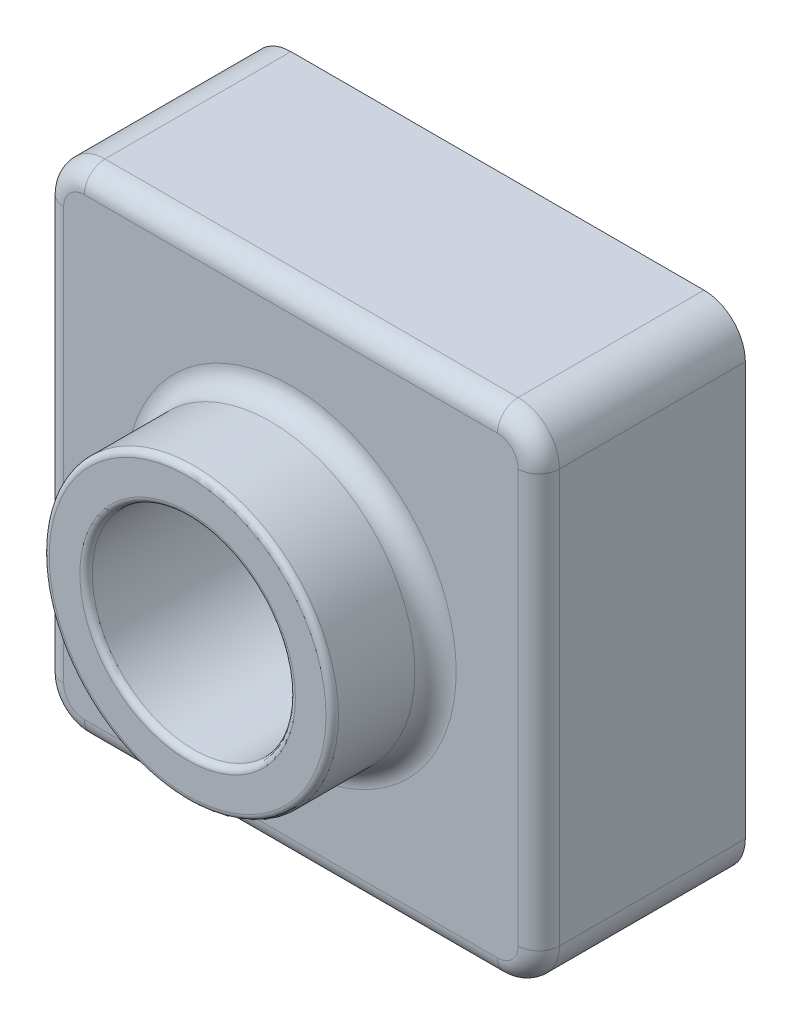
SolidWorks part; units mm, degrees
material "Chrome Stainless Steel"
ref_plane "Front Plane" through (0, 0, 0) normal (0, 0, 1) x (1, 0, 0)
ref_plane "Top Plane" through (0, 0, 0) normal (0, 1, 0) x (1, 0, 0)
ref_plane "Right Plane" through (0, 0, 0) normal (1, 0, 0) x (0, 0, -1)
sketch "Sketch1" plane through (0, 0, 0) normal (0, 0, 1) x (1, 0, 0)
  line L1 (0, 0) -> (-120, 0)
  line L2 (0, 0) -> (0, 120)
  line L3 (0, 120) -> (-120, 120)
  line L4 (-120, 0) -> (-120, 120)
  point P5 (0, 0)
  dimension "D1" = 120
  dimension "D2" = 120
extrude "Boss-Extrude1" add sketch "Sketch1" along normal blind 50
sketch "Sketch3" plane through (0, 0, 50) normal (0, 0, 1) x (1, 0, 0)
  line L0 (0, 120) -> (-120, 120) construction
  line L3 (-120, 120) -> (-120, 0) construction
  circle A0 centre (-60, 60) radius 35
  point P4 (0, 0)
  point P5 (0, 0)
  point P6 (-120, 39.2847)
  dimension "D1" = 70
  dimension "D2" = 60
  dimension "D3" = 60
extrude "Boss-Extrude2" add sketch "Sketch3" along normal blind 25 contours A0
sketch "Sketch8" plane through (0, 0, 75) normal (0, 0, 1) x (1, 0, 0)
  line L0 (0, 120) -> (-120, 120) construction
  line L1 (0, 0) -> (0, 120) construction
  circle A0 centre (-60, 60) radius 24.5852
  point P2 (-52.6384, 56.2286)
  point P7 (0, 0)
  dimension "D1" = 60
  dimension "D2" = 60
extrude "Cut-Extrude1" cut sketch "Sketch8" against normal through all contours A0
fillet "Fillet1" radius 10 4 edges at (-120, 0, 25) (0, 0, 25) (-120, 120, 25) (0, 120, 25)
fillet "Fillet2" radius 1.5 2 edges at (-25, 60, 75) (-35.4148, 60, 75)
fillet "Fillet3" radius 5 9 edges at (-117.0711, 117.0711, 50) (-60, 120, 50) (-2.9289, 117.0711, 50) (0, 60, 50) (-2.9289, 2.9289, 50) (-60, 0, 50) (-117.0711, 2.9289, 50) (-120, 60, 50) (-25, 60, 50)
shell "Shell1" thickness 2
